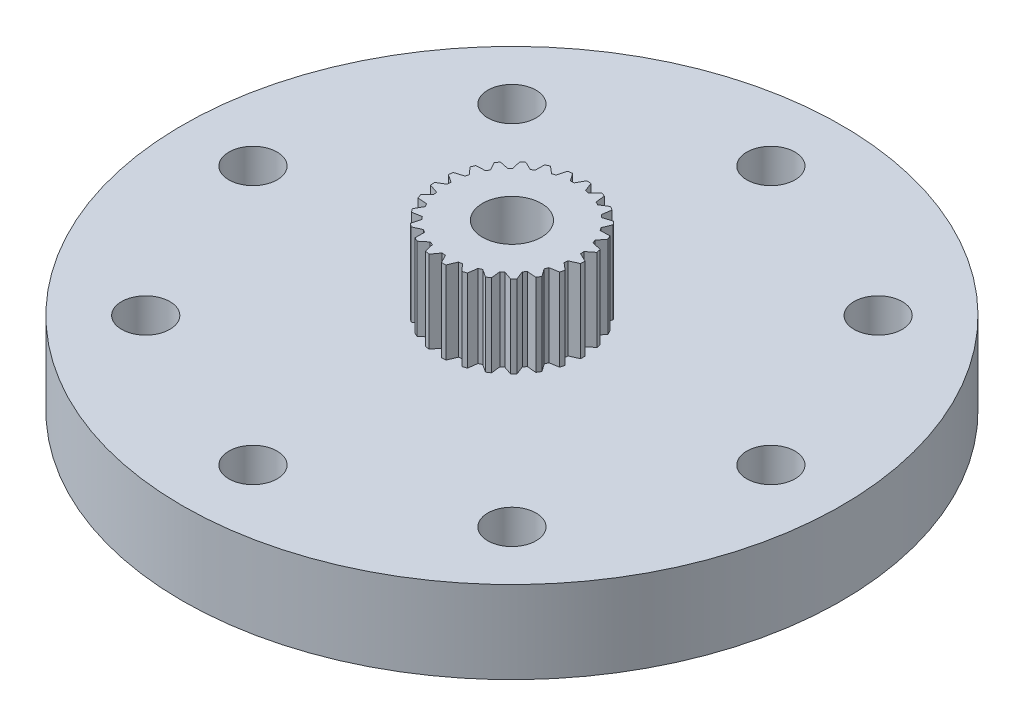
SolidWorks part; units mm, degrees
material "PLA"
ref_plane "Front Plane" through (0, 0, 0) normal (0, 0, 1) x (1, 0, 0)
ref_plane "Top Plane" through (0, 0, 0) normal (0, 1, 0) x (1, 0, 0)
ref_plane "Right Plane" through (0, 0, 0) normal (1, 0, 0) x (0, 0, -1)
sketch "Sketch1" plane through (0, 0, 0) normal (0, 1, 0) x (1, 0, 0)
  circle A0 centre (0, 0) radius 14
  dimension "D1" = 28
extrude "Boss-Extrude1" add sketch "Sketch1" along normal mid plane 3.5 contours A0
sketch "Sketch2" plane through (0, 1.75, 0) normal (0, 1, 0) x (1, 0, 0)
  line L0 (2.7822, 0.7455) -> (2.5435, 0.3349)
  line L1 (2.5435, 0.3349) -> (2.8804, 0)
  line L2 (2.8804, 0) -> (2.5435, -0.3349)
  line L3 (2.7822, -0.7455) -> (2.5435, -0.3349)
  line L4 (2.7822, -0.7455) -> (2.3701, -0.9817)
  line L5 (2.4945, -1.4402) -> (2.3701, -0.9817)
  line L6 (2.4945, -1.4402) -> (2.0353, -1.5617)
  line L7 (2.0367, -2.0367) -> (2.0353, -1.5617)
  line L8 (2.0367, -2.0367) -> (1.5617, -2.0353)
  line L9 (1.4402, -2.4945) -> (1.5617, -2.0353)
  line L10 (1.4402, -2.4945) -> (0.9817, -2.3701)
  line L11 (0.7455, -2.7822) -> (0.9817, -2.3701)
  line L12 (0.7455, -2.7822) -> (0.3349, -2.5435)
  line L13 (0, -2.8804) -> (0.3349, -2.5435)
  line L14 (0, -2.8804) -> (-0.3349, -2.5435)
  line L15 (-0.7455, -2.7822) -> (-0.3349, -2.5435)
  line L16 (-0.7455, -2.7822) -> (-0.9817, -2.3701)
  line L17 (-1.4402, -2.4945) -> (-0.9817, -2.3701)
  line L18 (-1.4402, -2.4945) -> (-1.5617, -2.0353)
  line L19 (-2.0367, -2.0367) -> (-1.5617, -2.0353)
  line L20 (-2.0367, -2.0367) -> (-2.0353, -1.5617)
  line L21 (-2.4945, -1.4402) -> (-2.0353, -1.5617)
  line L22 (-2.4945, -1.4402) -> (-2.3701, -0.9817)
  line L23 (-2.7822, -0.7455) -> (-2.3701, -0.9817)
  line L24 (-2.7822, -0.7455) -> (-2.5435, -0.3349)
  line L25 (-2.8804, 0) -> (-2.5435, -0.3349)
  line L26 (-2.8804, 0) -> (-2.5435, 0.3349)
  line L27 (-2.7822, 0.7455) -> (-2.5435, 0.3349)
  line L28 (-2.7822, 0.7455) -> (-2.3701, 0.9817)
  line L29 (-2.4945, 1.4402) -> (-2.3701, 0.9817)
  line L30 (-2.4945, 1.4402) -> (-2.0353, 1.5617)
  line L31 (-2.0367, 2.0367) -> (-2.0353, 1.5617)
  line L32 (-2.0367, 2.0367) -> (-1.5617, 2.0353)
  line L33 (-1.4402, 2.4945) -> (-1.5617, 2.0353)
  line L34 (-1.4402, 2.4945) -> (-0.9817, 2.3701)
  line L35 (-0.7455, 2.7822) -> (-0.9817, 2.3701)
  line L36 (-0.7455, 2.7822) -> (-0.3349, 2.5435)
  line L37 (0, 2.8804) -> (-0.3349, 2.5435)
  line L38 (0, 2.8804) -> (0.3349, 2.5435)
  line L39 (0.7455, 2.7822) -> (0.3349, 2.5435)
  line L40 (0.7455, 2.7822) -> (0.9817, 2.3701)
  line L41 (1.4402, 2.4945) -> (0.9817, 2.3701)
  line L42 (1.4402, 2.4945) -> (1.5617, 2.0353)
  line L43 (2.0367, 2.0367) -> (1.5617, 2.0353)
  line L44 (2.0367, 2.0367) -> (2.0353, 1.5617)
  line L45 (2.4945, 1.4402) -> (2.0353, 1.5617)
  line L46 (2.4945, 1.4402) -> (2.3701, 0.9817)
  line L47 (2.7822, 0.7455) -> (2.3701, 0.9817)
sketch "Sketch4" plane through (0, 1.75, 0) normal (0, 1, 0) x (1, 0, 0)
  circle A0 centre (0, 0) radius 5
  circle A1 centre (-7.7782, 7.7782) radius 1.025
  circle A2 centre (-7.7782, -7.7782) radius 1.025
  circle A3 centre (7.7782, -7.7782) radius 1.025
  circle A4 centre (7.7782, 7.7782) radius 1.025
  circle A5 centre (11, 0) radius 1.025
  circle A6 centre (0, -11) radius 1.025
  circle A7 centre (-11, 0) radius 1.025
  circle A8 centre (0, 11) radius 1.025
  circle A9 centre (0, 0) radius 14
hole_wizard "Tap Drill for M2.5x0.45 Tap1" positions "Sketch5" profile "Sketch6" hole size "M2.5x0.45" standard "ANSI Metric"
sketch "Sketch5" plane through (0, 1.75, 0) normal (0, 1, 0) x (1, 0, 0)
  point P0 (-11, 0)
  point P3 (-7.7782, 7.7782)
  point P6 (0, 11)
  point P9 (7.7782, 7.7782)
  point P12 (11, 0)
  point P15 (7.7782, -7.7782)
  point P18 (0, -11)
  point P21 (-7.7782, -7.7782)
sketch "Sketch6" plane through (-11, 1.75, 0) normal (1, 0, 0) x (0, 0, 1)
  line L0 (0, 0) -> (0, 6.6159)
  line L1 (0, 6.6159) -> (1.025, 6)
  line L2 (1.025, 6) -> (1.025, 0)
  line L5 (1.025, 0) -> (0, 0)
  line L10 (0, 6.6159) -> (-1.025, 6) construction
  line L11 (0, -6.35) -> (0, 107.95) construction
  dimension "Hole Dia." = 2.05
  dimension "Hole Depth" = 6
  dimension "Drill Angle" = 118
sketch "Sketch7" plane through (0, -1.75, 0) normal (0, -1, 0) x (1, 0, 0)
  circle A0 centre (0, 0) radius 5
  dimension "D1" = 10
extrude "Cut-Extrude1" cut sketch "Sketch7" against normal blind 2.3
sketch "Sketch8" plane through (0, 1.75, 0) normal (0, 1, 0) x (1, 0, 0)
  line L0 (-0.1289, -2.6969) -> (0.0574, -3.0495)
  line L1 (-0.2813, -2.6853) -> (-0.5188, -3.0056)
  line L2 (-0.7955, -2.5802) -> (-0.7028, -2.9679)
  line L3 (-0.9403, -2.531) -> (-1.2499, -2.7821)
  line L4 (-1.4122, -2.3013) -> (-1.4188, -2.6999)
  line L5 (-1.5401, -2.2176) -> (-1.9025, -2.3839)
  line L6 (-1.9401, -1.8778) -> (-2.0457, -2.2622)
  line L7 (-2.0433, -1.765) -> (-2.4356, -1.8358)
  line L8 (-2.3461, -1.3363) -> (-2.544, -1.6824)
  line L9 (-2.418, -1.2014) -> (-2.8156, -1.1725)
  line L10 (-2.6047, -0.7108) -> (-2.8825, -0.9969)
  line L11 (-2.6408, -0.5623) -> (-3.0188, -0.4354)
  line L12 (-2.6997, -0.0407) -> (-3.0398, -0.2487)
  line L13 (-2.6977, 0.1121) -> (-3.0322, 0.329)
  line L14 (-2.625, 0.6319) -> (-3.0062, 0.5151)
  line L15 (-2.585, 0.7795) -> (-2.8551, 1.0728)
  line L16 (-2.3854, 1.2649) -> (-2.7837, 1.2465)
  line L17 (-2.31, 1.3979) -> (-2.4986, 1.7491)
  line L18 (-1.9959, 1.8184) -> (-2.3862, 1.8996)
  line L19 (-1.8898, 1.9284) -> (-1.9852, 2.3155)
  line L20 (-1.481, 2.2576) -> (-1.8388, 2.4334)
  line L21 (-1.3508, 2.3378) -> (-1.3469, 2.7365)
  line L22 (-0.873, 2.555) -> (-1.1759, 2.8142)
  line L23 (-0.727, 2.6003) -> (-0.6241, 2.9855)
  line L24 (-0.2102, 2.6918) -> (-0.4391, 3.0182)
  line L25 (-0.0575, 2.6994) -> (0.138, 3.0469)
  line L26 (0.4659, 2.6595) -> (0.3253, 3.0326)
  line L27 (0.6156, 2.6289) -> (0.8914, 2.9168)
  line L28 (1.1126, 2.4601) -> (1.0693, 2.8564)
  line L29 (1.2501, 2.3932) -> (1.5887, 2.6035)
  line L30 (1.6895, 2.1061) -> (1.746, 2.5008)
  line L31 (1.8059, 2.0071) -> (2.1863, 2.1266)
  line L32 (2.1601, 1.6198) -> (2.3131, 1.988)
  line L33 (2.2484, 1.4949) -> (2.6465, 1.5161)
  line L34 (2.4951, 1.0317) -> (2.7348, 1.3503)
  line L35 (2.5495, 0.8888) -> (2.9404, 0.8103)
  line L36 (2.6733, 0.3788) -> (2.9847, 0.6277)
  line L37 (2.6905, 0.2269) -> (3.0495, 0.0536)
  line L38 (2.6835, -0.2979) -> (3.047, -0.1342)
  line L39 (2.6623, -0.4493) -> (2.9671, -0.7065)
  line L40 (2.5251, -0.9559) -> (2.9179, -0.8878)
  line L41 (2.467, -1.0973) -> (2.6982, -1.4221)
  line L42 (2.208, -1.5539) -> (2.6055, -1.5856)
  line L43 (2.1166, -1.6764) -> (2.2597, -2.0485)
  line L44 (1.7522, -2.0542) -> (2.1293, -2.1837)
  line L45 (1.6332, -2.1501) -> (1.6793, -2.5461)
  line L46 (1.1863, -2.4254) -> (1.5193, -2.6446)
  line L47 (1.0472, -2.4887) -> (0.9934, -2.8837)
  line L48 (0.5459, -2.6442) -> (0.8139, -2.9394)
  line L49 (0.3954, -2.6709) -> (0.245, -3.0401)
  arc A0 (-0.2813, -2.6853) -> (-0.1289, -2.6969) centre (0, 0) ccw
  arc A1 (-0.7028, -2.9679) -> (-0.5188, -3.0056) centre (0, 0) ccw
  arc A2 (-0.9403, -2.531) -> (-0.7955, -2.5802) centre (0, 0) ccw
  arc A3 (-1.4188, -2.6999) -> (-1.2499, -2.7821) centre (0, 0) ccw
  arc A4 (-1.5401, -2.2176) -> (-1.4122, -2.3013) centre (0, 0) ccw
  arc A5 (-2.0457, -2.2622) -> (-1.9025, -2.3839) centre (0, 0) ccw
  arc A6 (-2.0433, -1.765) -> (-1.9401, -1.8778) centre (0, 0) ccw
  arc A7 (-2.544, -1.6824) -> (-2.4356, -1.8358) centre (0, 0) ccw
  arc A8 (-2.418, -1.2014) -> (-2.3461, -1.3363) centre (0, 0) ccw
  arc A9 (-2.8825, -0.9969) -> (-2.8156, -1.1725) centre (0, 0) ccw
  arc A10 (-2.6408, -0.5623) -> (-2.6047, -0.7108) centre (0, 0) ccw
  arc A11 (-3.0398, -0.2487) -> (-3.0188, -0.4354) centre (0, 0) ccw
  arc A12 (-2.6977, 0.1121) -> (-2.6997, -0.0407) centre (0, 0) ccw
  arc A13 (-3.0062, 0.5151) -> (-3.0322, 0.329) centre (0, 0) ccw
  arc A14 (-2.585, 0.7795) -> (-2.625, 0.6319) centre (0, 0) ccw
  arc A15 (-2.7837, 1.2465) -> (-2.8551, 1.0728) centre (0, 0) ccw
  arc A16 (-2.31, 1.3979) -> (-2.3854, 1.2649) centre (0, 0) ccw
  arc A17 (-2.3862, 1.8996) -> (-2.4986, 1.7491) centre (0, 0) ccw
  arc A18 (-1.8898, 1.9284) -> (-1.9959, 1.8184) centre (0, 0) ccw
  arc A19 (-1.8388, 2.4334) -> (-1.9852, 2.3155) centre (0, 0) ccw
  arc A20 (-1.3508, 2.3378) -> (-1.481, 2.2576) centre (0, 0) ccw
  arc A21 (-1.1759, 2.8142) -> (-1.3469, 2.7365) centre (0, 0) ccw
  arc A22 (-0.727, 2.6003) -> (-0.873, 2.555) centre (0, 0) ccw
  arc A23 (-0.4391, 3.0182) -> (-0.6241, 2.9855) centre (0, 0) ccw
  arc A24 (-0.0575, 2.6994) -> (-0.2102, 2.6918) centre (0, 0) ccw
  arc A25 (0.3253, 3.0326) -> (0.138, 3.0469) centre (0, 0) ccw
  arc A26 (0.6156, 2.6289) -> (0.4659, 2.6595) centre (0, 0) ccw
  arc A27 (1.0693, 2.8564) -> (0.8914, 2.9168) centre (0, 0) ccw
  arc A28 (1.2501, 2.3932) -> (1.1126, 2.4601) centre (0, 0) ccw
  arc A29 (1.746, 2.5008) -> (1.5887, 2.6035) centre (0, 0) ccw
  arc A30 (1.8059, 2.0071) -> (1.6895, 2.1061) centre (0, 0) ccw
  arc A31 (2.3131, 1.988) -> (2.1863, 2.1266) centre (0, 0) ccw
  arc A32 (2.2484, 1.4949) -> (2.1601, 1.6198) centre (0, 0) ccw
  arc A33 (2.7348, 1.3503) -> (2.6465, 1.5161) centre (0, 0) ccw
  arc A34 (2.5495, 0.8888) -> (2.4951, 1.0317) centre (0, 0) ccw
  arc A35 (2.9847, 0.6277) -> (2.9404, 0.8103) centre (0, 0) ccw
  arc A36 (2.6905, 0.2269) -> (2.6733, 0.3788) centre (0, 0) ccw
  arc A37 (3.047, -0.1342) -> (3.0495, 0.0536) centre (0, 0) ccw
  arc A38 (2.6623, -0.4493) -> (2.6835, -0.2979) centre (0, 0) ccw
  arc A39 (2.9179, -0.8878) -> (2.9671, -0.7065) centre (0, 0) ccw
  arc A40 (2.467, -1.0973) -> (2.5251, -0.9559) centre (0, 0) ccw
  arc A41 (2.6055, -1.5856) -> (2.6982, -1.4221) centre (0, 0) ccw
  arc A42 (2.1166, -1.6764) -> (2.208, -1.5539) centre (0, 0) ccw
  arc A43 (2.1293, -2.1837) -> (2.2597, -2.0485) centre (0, 0) ccw
  arc A44 (1.6332, -2.1501) -> (1.7522, -2.0542) centre (0, 0) ccw
  arc A45 (1.5193, -2.6446) -> (1.6793, -2.5461) centre (0, 0) ccw
  arc A46 (1.0472, -2.4887) -> (1.1863, -2.4254) centre (0, 0) ccw
  arc A47 (0.8139, -2.9394) -> (0.9934, -2.8837) centre (0, 0) ccw
  arc A48 (0.3954, -2.6709) -> (0.5459, -2.6442) centre (0, 0) ccw
  arc A49 (0.0574, -3.0495) -> (0.245, -3.0401) centre (0, 0) ccw
extrude "Boss-Extrude3" add sketch "Sketch8" along normal blind 3.5
hole_wizard "Tap Drill for M3x0.5 Tap1" positions "Sketch9" profile "Sketch10" hole size "M3x0.5" standard "ANSI Metric"
sketch "Sketch9" plane through (0, 5.25, 0) normal (0, 1, 0) x (1, 0, 0)
  point P0 (0, 0)
sketch "Sketch10" plane through (0, 5.25, 0) normal (1, 0, 0) x (0, 0, 1)
  line L0 (0, 0) -> (0, 6.7511)
  line L1 (0, 6.7511) -> (1.25, 6)
  line L2 (1.25, 6) -> (1.25, 0)
  line L5 (1.25, 0) -> (0, 0)
  line L10 (0, 6.7511) -> (-1.25, 6) construction
  line L11 (0, -6.35) -> (0, 107.95) construction
  dimension "Hole Dia." = 2.5
  dimension "Hole Depth" = 6
  dimension "Drill Angle" = 118
